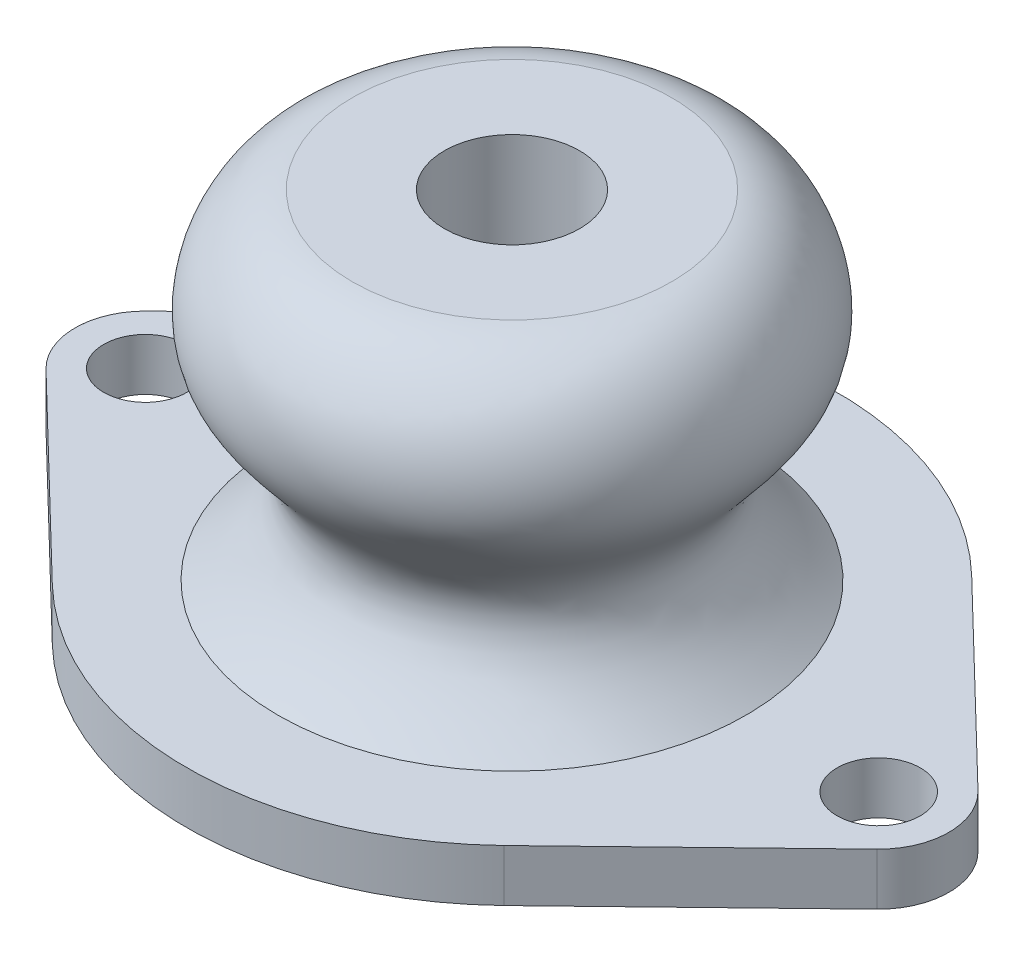
SolidWorks part; units mm, degrees
ref_plane "Front Plane" through (0, 0, 0) normal (0, 0, 1) x (1, 0, 0)
ref_plane "Top Plane" through (0, 0, 0) normal (0, 1, 0) x (1, 0, 0)
ref_plane "Right Plane" through (0, 0, 0) normal (1, 0, 0) x (0, 0, -1)
sketch "Sketch1" plane through (0, 0, 0) normal (0, 1, 0) x (1, 0, 0)
  line L0 (-17.907, 0) -> (17.907, 0) construction
  line L1 (-20.2903, 2.4654) -> (-11.0337, 11.4137)
  line L2 (-20.2903, -2.4654) -> (-11.0337, -11.4137)
  line L3 (11.0337, -11.4137) -> (20.2903, -2.4654)
  line L4 (20.2903, 2.4654) -> (11.0337, 11.4137)
  circle A0 centre (0, 0) radius 11.43 construction
  circle A1 centre (-17.907, 0) radius 2.032
  circle A2 centre (17.907, 0) radius 2.032
  circle A3 centre (0, 0) radius 3.302
  circle A4 centre (0, 0) radius 21.336 construction
  arc A5 (-11.0337, -11.4137) -> (11.0337, -11.4137) centre (0, 0) ccw construction
  arc A6 (-20.2903, 2.4654) -> (-20.2903, -2.4654) centre (-17.907, 0) ccw construction
  arc A7 (20.2903, -2.4654) -> (20.2903, 2.4654) centre (17.907, 0) ccw construction
  arc A8 (20.2903, -2.4654) -> (20.2903, 2.4654) centre (17.907, 0) ccw
  arc A9 (-20.2903, 2.4654) -> (-20.2903, -2.4654) centre (-17.907, 0) ccw
  arc A10 (-11.0337, -11.4137) -> (11.0337, -11.4137) centre (0, 0) ccw
  arc A11 (11.0337, 11.4137) -> (-11.0337, 11.4137) centre (0, 0) ccw construction
  arc A12 (11.0337, 11.4137) -> (-11.0337, 11.4137) centre (0, 0) ccw
  point P5 (0, 0)
  dimension "D1" = 4.064
  dimension "D3" = 22.86
  dimension "D4" = 6.604
  dimension "D5" = 42.672
  dimension "D6" = 31.75
  dimension "D2" = 35.814
extrude "Boss-Extrude1" add sketch "Sketch1" along normal blind 2.54
sketch "Sketch3" plane through (0, 0, 0) normal (1, 0, 0) x (0, 0, -1)
  line L0 (0, 2.54) -> (0, 12.7) construction
  line L1 (-3.302, 19.05) -> (-7.795, 19.05)
  line L2 (-2.4654, 2.54) -> (-11.4137, 2.54) construction
  line L3 (2.4654, 2.54) -> (-2.4654, 2.54) construction
  line L4 (-7.62, 2.54) -> (-11.43, 2.54)
  line L5 (0, 12.7) -> (0, 2.54) construction
  line L6 (0, 2.54) -> (0, 12.7) construction
  line L7 (0, 19.05) -> (0, 2.54) construction
  line L11 (-3.302, 19.05) -> (-3.302, 12.7)
  line L12 (-3.302, 12.7) -> (-7.62, 12.7)
  line L13 (0, 12.7) -> (0, 2.54) construction
  line L17 (-7.62, 12.7) -> (-7.62, 2.54)
  spline S0 degree 3 poles (-7.795, 19.05) (-10.7406, 18.6451) (-14.5194, 10.3959) (-5.0185, 7.762) (-11.43, 2.54) knots 0 0 0 0 0.449938 1 1 1 1
  dimension "D2" = 11.43
  dimension "D3" = 6.35
  dimension "D4" = 7.62
  dimension "D5" = 3.302
revolve "Revolve1" add sketch "Sketch3" angle 360 about L7
